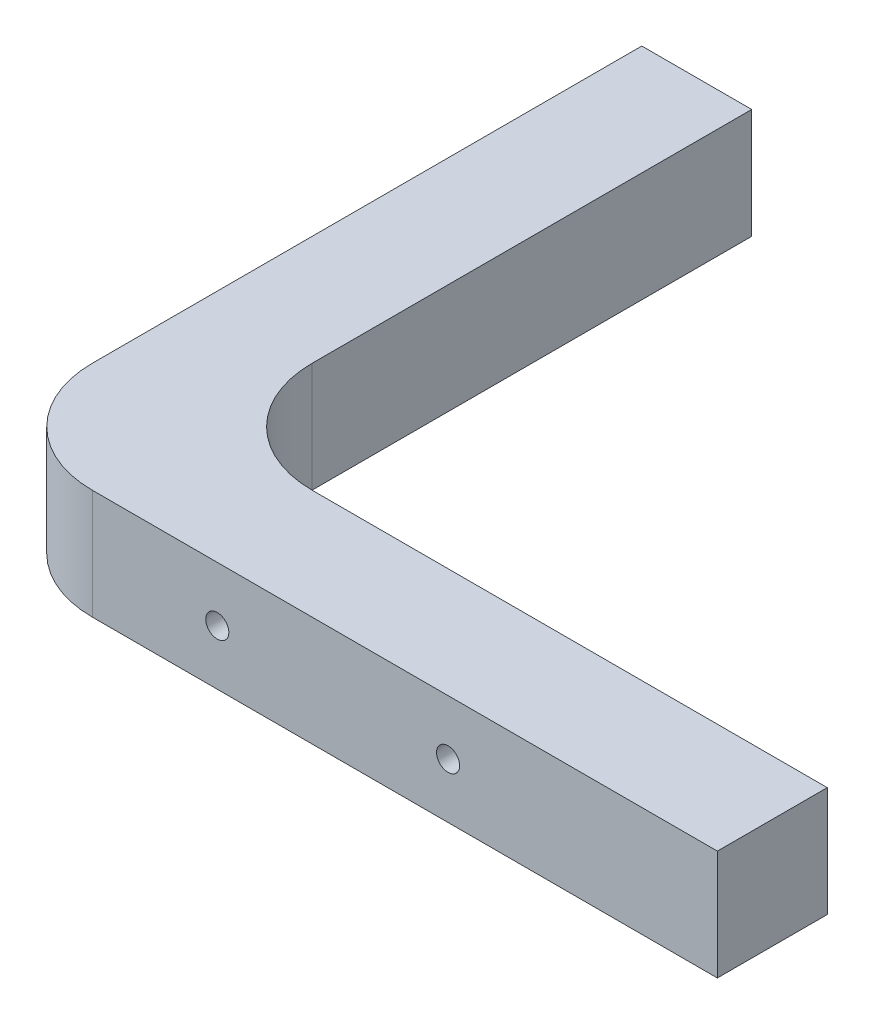
SolidWorks part; units mm, degrees
material "PTFE (general)"
ref_plane "Front Plane" through (0, 0, 0) normal (0, 0, 1) x (1, 0, 0)
ref_plane "Top Plane" through (0, 0, 0) normal (0, 1, 0) x (1, 0, 0)
ref_plane "Right Plane" through (0, 0, 0) normal (1, 0, 0) x (0, 0, -1)
sketch "Sketch1" plane through (0, 0, 0) normal (0, 1, 0) x (1, 0, 0)
  line L0 (-113.75, 10) -> (0, 10)
  line L1 (0, 10) -> (0, -10)
  line L2 (0, -10) -> (-133.75, -10)
  line L4 (-133.75, -10) -> (-133.75, 110)
  line L5 (-133.75, 110) -> (-113.75, 110)
  line L6 (-113.75, 110) -> (-113.75, 10)
  point P5 (0, 0)
  dimension "D1" = 133.75
  dimension "D2" = 20
  dimension "D3" = 120
  dimension "D4" = 20
extrude "Boss-Extrude1" add sketch "Sketch1" along normal blind 20
fillet "Fillet1" radius 20 2 edges at (-133.75, 10, 10) (-113.75, 10, -10)
sketch "Sketch2" plane through (0, 0, -10) normal (0, 0, -1) x (-1, 0, 0)
  line L0 (0, 10) -> (93.75, 10) construction
  line L1 (0, 20) -> (0, 0) construction
  line L2 (93.75, 0) -> (93.75, 20) construction
  line L3 (70, 20) -> (70, 0) construction
  line L4 (0, 20) -> (93.75, 20) construction
  line L5 (0, 0) -> (93.75, 0) construction
  circle A0 centre (49, 10) radius 2.1
  circle A1 centre (91, 10) radius 2.1
  dimension "D1" = 4.2
  dimension "D4" = 4.2
  dimension "D2" = 70
  dimension "D3" = 21
  dimension "D5" = 21
extrude "Cut-Extrude1" cut sketch "Sketch2" against normal up to surface (20 mm away) up to face at (-56.875, 10, 10)
